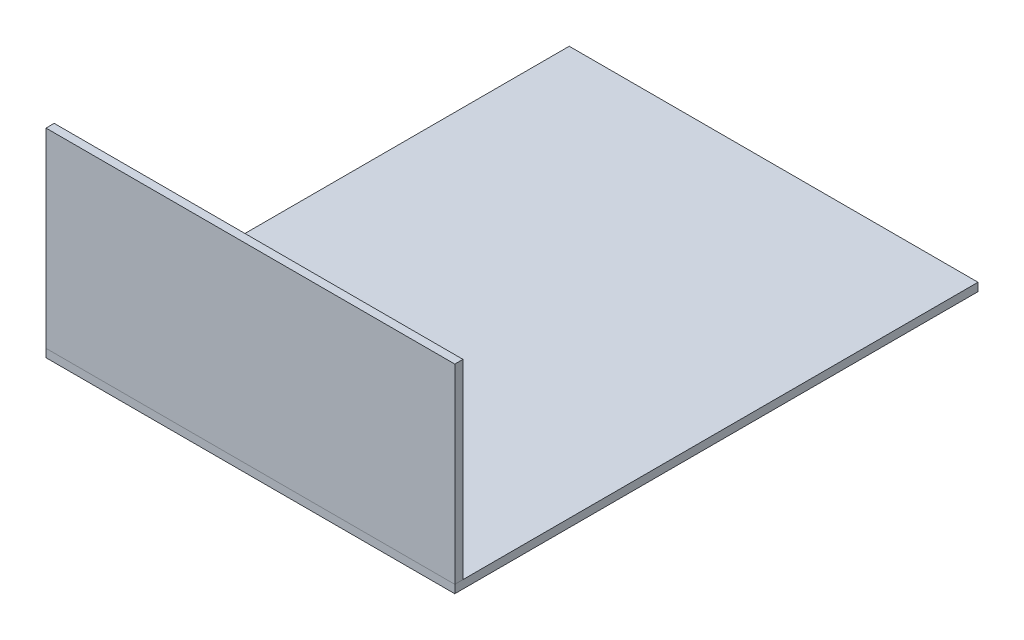
SolidWorks part; units mm, degrees
ref_plane "Front Plane" through (0, 0, 0) normal (0, 0, 1) x (1, 0, 0)
ref_plane "Top Plane" through (0, 0, 0) normal (0, 1, 0) x (1, 0, 0)
ref_plane "Right Plane" through (0, 0, 0) normal (1, 0, 0) x (0, 0, -1)
sketch "Sketch1" plane through (0, 0, 0) normal (0, 1, 0) x (1, 0, 0)
  line L1 (-150, 192) -> (150, 192)
  line L2 (-150, 192) -> (-150, -192)
  line L3 (-150, -192) -> (150, -192)
  line L4 (150, 192) -> (150, -192)
  line L5 (-150, 192) -> (150, -192) construction
  line L6 (-150, -192) -> (150, 192) construction
  point P0 (0, 0)
  dimension "D1" = 300
  dimension "D2" = 384
extrude "Boss-Extrude1" add sketch "Sketch1" along normal blind 6
sketch "Sketch2" plane through (0, 6, 0) normal (0, 1, 0) x (1, 0, 0)
  line L0 (150, -192) -> (150, 192) construction
  line L1 (-150, -192) -> (150, -192)
  line L2 (-150, -192) -> (-150, -186)
  line L3 (-150, -186) -> (150, -186)
  line L4 (150, -192) -> (150, -186)
  dimension "D1" = 6
extrude "Boss-Extrude2" add sketch "Sketch2" along normal blind 140 separate body
